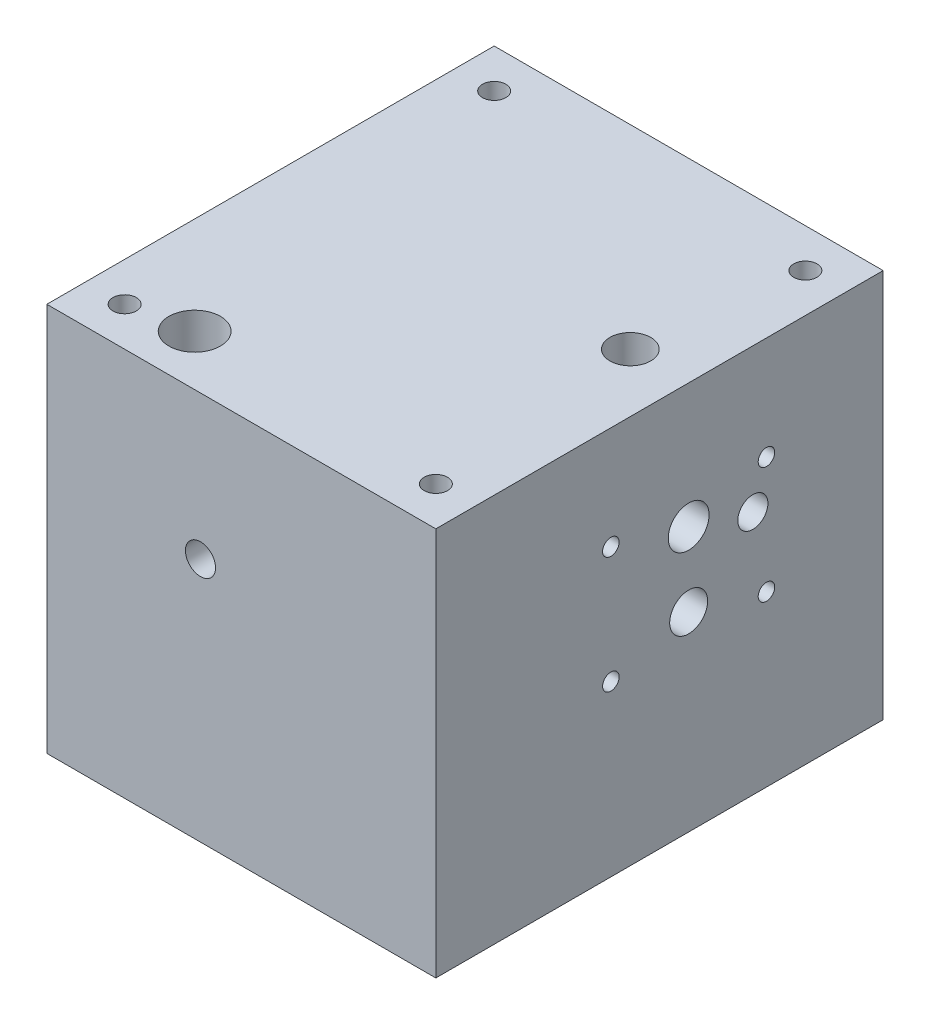
SolidWorks part; units mm, degrees
ref_plane "前视基准面" through (0, 0, 0) normal (0, 0, 1) x (1, 0, 0)
ref_plane "上视基准面" through (0, 0, 0) normal (0, 1, 0) x (1, 0, 0)
ref_plane "右视基准面" through (0, 0, 0) normal (1, 0, 0) x (0, 0, -1)
sketch "草图1" plane through (0, 0, 0) normal (0, 1, 0) x (1, 0, 0)
  line L1 (100, -100) -> (-100, -100)
  line L2 (100, -100) -> (100, 100)
  line L3 (100, 100) -> (-100, 100)
  line L4 (-100, -100) -> (-100, 100)
  line L5 (100, -100) -> (-100, 100) construction
  line L6 (100, 100) -> (-100, -100) construction
  point P0 (0, 0)
  dimension "D1" = 200
  dimension "D2" = 200
extrude "凸台-拉伸1" add sketch "草图1" along normal blind 200
sketch "草图9" plane through (100, 0, 0) normal (1, 0, 0) x (0, 0, -1)
  line L0 (0, 117) -> (0, 19.4773) construction
  line L1 (51, 74) -> (-51, 74)
  line L2 (51, 74) -> (51, 160)
  line L3 (51, 160) -> (-51, 160)
  line L4 (-51, 74) -> (-51, 160)
  line L5 (51, 74) -> (-51, 160) construction
  line L6 (51, 160) -> (-51, 74) construction
  line L7 (100, 200) -> (100, 0) construction
  line L8 (0, 117) -> (-57.0715, 117) construction
  line L9 (-100, 200) -> (100, 200) construction
  circle A0 centre (0, 136) radius 16.5
  circle A1 centre (0, 136) radius 16.5
  circle A2 centre (33, 126) radius 10
  circle A3 centre (0, 98) radius 16.5
  point P0 (-40, 147)
  point P1 (0, 117)
  point P2 (0, 117)
  point P7 (0, 136)
  point P8 (-40, 87)
  point P11 (0, 136)
  point P12 (40, 147)
  point P13 (40, 87)
  point P23 (33, 126)
  dimension "D14" = 33
  dimension "D15" = 33
  dimension "D19" = 20
  dimension "D21" = 33
  dimension "D1" = 86
  dimension "D2" = 102
  dimension "D3" = 100
  dimension "D4" = 40
  dimension "D5" = 40
  dimension "D6" = 30
  dimension "D7" = 30
  dimension "D8" = 30
  dimension "D9" = 30
  dimension "D10" = 11
  dimension "D11" = 40
  dimension "D12" = 19
  dimension "D13" = 19
  dimension "D16" = 40
  dimension "D17" = 9
  dimension "D18" = 33
  dimension "D20" = 38
hole_wizard "M10 螺纹孔1" positions "草图10" profile "草图11" tap size "M10" standard "GB"
sketch "草图10" plane through (100, 0, 0) normal (1, 0, 0) x (0, 0, -1)
  point P0 (-40, 87)
  point P3 (-40, 147)
  point P6 (40, 147)
  point P9 (40, 87)
sketch "草图11" plane through (100, 87, 40) normal (0, 1, 0) x (0, 0, -1)
  line L0 (0, 0) -> (0, 19.5537)
  line L1 (0, 19.5537) -> (4.25, 17)
  line L2 (4.25, 17) -> (4.25, 0)
  line L5 (4.25, 0) -> (0, 0)
  line L10 (0, 19.5537) -> (-4.25, 17) construction
  line L11 (0, -6.35) -> (0, 107.95) construction
  dimension "螺纹孔钻头直径" = 8.5
  dimension "螺纹孔钻头深度" = 17
  dimension "导头角度" = 118
cosmetic thread "孔螺蚊线5" parameters "D1"=17, "D2"=10
cosmetic thread "孔螺蚊线6" parameters "D1"=17, "D2"=10
cosmetic thread "孔螺蚊线7" parameters "D1"=17, "D2"=10
cosmetic thread "孔螺蚊线8" parameters "D1"=17, "D2"=10
sketch "草图12" plane through (0, 0, -100) normal (0, 0, -1) x (-1, 0, 0)
  line L0 (-100, 200) -> (-100, 0) construction
  line L1 (173, 43.5) -> (-173, 43.5)
  line L2 (173, 43.5) -> (173, 116.5)
  line L3 (173, 116.5) -> (-173, 116.5)
  line L4 (-173, 43.5) -> (-173, 116.5)
  line L5 (173, 43.5) -> (-173, 116.5) construction
  line L6 (173, 116.5) -> (-173, 43.5) construction
  line L7 (-68, 116.5) -> (-68, 43.5)
  line L8 (68, 116.5) -> (68, 43.5)
  line L9 (-100, 200) -> (100, 200) construction
  circle A0 centre (0, 62) radius 12.5
  circle A1 centre (0, 62) radius 9
  circle A2 centre (-21, 98) radius 9
  circle A3 centre (-21, 98) radius 12.5
  circle A4 centre (21, 98) radius 9
  circle A5 centre (21, 98) radius 12.5
  circle A6 centre (42, 62) radius 9
  circle A7 centre (42, 62) radius 12.5
  point P0 (0, 80)
  point P11 (44, 107)
  point P12 (21, 53)
  point P13 (-44, 107)
  point P14 (-21, 53)
  point P17 (0, 62)
  point P19 (-21, 98)
  point P22 (21, 98)
  point P31 (42, 62)
  dimension "D16" = 18
  dimension "D17" = 25
  dimension "D22" = 25
  dimension "D23" = 18
  dimension "D24" = 18
  dimension "D25" = 25
  dimension "D27" = 18
  dimension "D28" = 25
  dimension "D1" = 346
  dimension "D2" = 100
  dimension "D3" = 68
  dimension "D4" = 68
  dimension "D5" = 27
  dimension "D6" = 27
  dimension "D7" = 27
  dimension "D8" = 27
  dimension "D9" = 73
  dimension "D10" = 21
  dimension "D11" = 21
  dimension "D12" = 44
  dimension "D13" = 44
  dimension "D14" = 156.5
  dimension "D15" = 18
  dimension "D18" = 18
  dimension "D19" = 18
  dimension "D20" = 21
  dimension "D21" = 21
  dimension "D26" = 42
  dimension "D29" = 138
hole_wizard "M8 螺纹孔1" positions "草图13" profile "草图14" tap size "M8" standard "GB"
sketch "草图13" plane through (0, 0, -100) normal (0, 0, -1) x (-1, 0, 0)
  point P0 (-44, 107)
  point P3 (-21, 53)
  point P6 (21, 53)
  point P9 (44, 107)
sketch "草图14" plane through (44, 107, -100) normal (1, 0, 0) x (0, 1, 0)
  line L0 (0, 0) -> (0, 27.0429)
  line L1 (0, 27.0429) -> (3.4, 25)
  line L2 (3.4, 25) -> (3.4, 0)
  line L5 (3.4, 0) -> (0, 0)
  line L10 (0, 27.0429) -> (-3.4, 25) construction
  line L11 (0, -6.35) -> (0, 107.95) construction
  dimension "螺纹孔钻头直径" = 6.8
  dimension "螺纹孔钻头深度" = 25
  dimension "导头角度" = 118
cosmetic thread "孔螺蚊线9" parameters "D1"=16, "D2"=8
cosmetic thread "孔螺蚊线10" parameters "D1"=16, "D2"=8
cosmetic thread "孔螺蚊线11" parameters "D1"=16, "D2"=8
cosmetic thread "孔螺蚊线12" parameters "D1"=16, "D2"=8
sketch "草图16" plane through (-100, 0, 0) normal (-1, 0, 0) x (0, 0, 1)
  line L0 (-67.5744, 98.0404) -> (-50, 98.0404) construction
  line L5 (-50, 138) -> (56, 138)
  line L6 (-50, 138) -> (-50, 58)
  line L7 (-50, 58) -> (56, 58)
  line L8 (56, 138) -> (56, 58)
  line L9 (56, 98.0404) -> (97.1803, 98.0404) construction
  line L11 (-100, 200) -> (100, 200) construction
  circle A0 centre (0, 98.0404) radius 6
  circle A1 centre (0, 98.0404) radius 10
  circle A2 centre (-25, 98) radius 6
  circle A3 centre (-25, 98) radius 10
  point P4 (0, 98.0404)
  point P7 (23, 71.0404)
  point P8 (23, 125.0404)
  point P9 (-31, 125.0404)
  point P10 (-31, 71.0404)
  point P18 (-25, 98)
  dimension "D13" = 20
  dimension "D14" = 12
  dimension "D17" = 20
  dimension "D18" = 12
  dimension "D1" = 106
  dimension "D2" = 80
  dimension "D3" = 56
  dimension "D4" = 27
  dimension "D5" = 27
  dimension "D6" = 27
  dimension "D7" = 27
  dimension "D8" = 23
  dimension "D9" = 23
  dimension "D10" = 54
  dimension "D11" = 54
  dimension "D12" = 62
  dimension "D15" = 40
  dimension "D16" = 48
  dimension "D19" = 75
hole_wizard "M14 螺纹孔2" positions "草图19" profile "草图18" tap size "M14" standard "IS"
sketch "草图19" plane through (-100, 0, 0) normal (-1, 0, 0) x (0, 0, 1)
  point P0 (23, 125.0404)
  point P3 (-31, 125.0404)
  point P6 (-31, 71.0404)
  point P9 (23, 71.0404)
sketch "草图18" plane through (-100, 125.0404, 23) normal (0, 1, 0) x (0, 0, 1)
  line L0 (0, 0) -> (0, 20.6052)
  line L1 (0, 20.6052) -> (6, 17)
  line L2 (6, 17) -> (6, 0)
  line L5 (6, 0) -> (0, 0)
  line L10 (0, 20.6052) -> (-6, 17) construction
  line L11 (0, -6.35) -> (0, 107.95) construction
  dimension "螺纹孔钻头直径" = 12
  dimension "螺纹孔钻头深度" = 17
  dimension "导头角度" = 118
cosmetic thread "孔螺蚊线13" parameters "D1"=17, "D2"=14
cosmetic thread "孔螺蚊线14" parameters "D1"=17, "D2"=14
cosmetic thread "孔螺蚊线15" parameters "D1"=17, "D2"=14
cosmetic thread "孔螺蚊线16" parameters "D1"=17, "D2"=14
sketch "草图22" plane through (0, 200, 0) normal (0, 1, 0) x (1, 0, 0)
  line L0 (100, -100) -> (100, 100) construction
  line L1 (-173, 100) -> (173, 100) construction
  point P0 (70, 0)
  dimension "D1" = 30
  dimension "D2" = 100
hole_wizard "M24 螺纹孔的螺纹孔钻头1" positions "草图25" profile "草图26" hole size "M24" standard "IS"
sketch "草图25" plane through (0, 200, 0) normal (0, 1, 0) x (1, 0, 0)
  point P0 (70, 0)
sketch "草图26" plane through (70, 200, 0) normal (1, 0, 0) x (0, 0, 1)
  line L0 (0, 0) -> (0, 66.309)
  line L1 (0, 66.309) -> (10.5, 60)
  line L2 (10.5, 60) -> (10.5, 0)
  line L5 (10.5, 0) -> (0, 0)
  line L10 (0, 66.309) -> (-10.5, 60) construction
  line L11 (0, -6.35) -> (0, 107.95) construction
  dimension "孔直径" = 21
  dimension "孔深度" = 60
  dimension "导头角度" = 118
hole_wizard "M24 螺纹孔的螺纹孔钻头2" positions "草图29" profile "草图30" hole size "M24" standard "IS"
sketch "草图29" plane through (100, 0, 0) normal (1, 0, 0) x (0, 0, -1)
  point P0 (0, 136)
sketch "草图30" plane through (100, 136, 0) normal (0, 1, 0) x (0, 0, -1)
  line L0 (0, 0) -> (0, 48.309)
  line L1 (0, 48.309) -> (10.5, 42)
  line L2 (10.5, 42) -> (10.5, 0)
  line L5 (10.5, 0) -> (0, 0)
  line L10 (0, 48.309) -> (-10.5, 42) construction
  line L11 (0, -6.35) -> (0, 107.95) construction
  dimension "孔直径" = 21
  dimension "孔深度" = 42
  dimension "导头角度" = 118
hole_wizard "M22 螺纹孔的螺纹孔钻头1" positions "草图31" profile "草图32" hole size "M22" standard "IS"
sketch "草图31" plane through (0, 0, -100) normal (0, 0, -1) x (-1, 0, 0)
  point P0 (-21, 98)
sketch "草图32" plane through (21, 98, -100) normal (1, 0, 0) x (0, 1, 0)
  line L0 (0, 0) -> (0, 116.8584)
  line L1 (0, 116.8584) -> (9.75, 111)
  line L2 (9.75, 111) -> (9.75, 0)
  line L5 (9.75, 0) -> (0, 0)
  line L10 (0, 116.8584) -> (-9.75, 111) construction
  line L11 (0, -6.35) -> (0, 107.95) construction
  dimension "孔直径" = 19.5
  dimension "孔深度" = 111
  dimension "导头角度" = 118
hole_wizard "M22 螺纹孔的螺纹孔钻头3" positions "草图35" profile "草图36" hole size "M22" standard "IS"
sketch "草图35" plane through (-100, 0, 0) normal (-1, 0, 0) x (0, 0, 1)
  point P0 (-25, 98)
sketch "草图36" plane through (-100, 98, -25) normal (0, 1, 0) x (0, 0, 1)
  line L0 (0, 0) -> (0, 95.8584)
  line L1 (0, 95.8584) -> (9.75, 90)
  line L2 (9.75, 90) -> (9.75, 0)
  line L5 (9.75, 0) -> (0, 0)
  line L10 (0, 95.8584) -> (-9.75, 90) construction
  line L11 (0, -6.35) -> (0, 107.95) construction
  dimension "孔直径" = 19.5
  dimension "孔深度" = 90
  dimension "导头角度" = 118
hole_wizard "M22 螺纹孔的螺纹孔钻头4" positions "草图37" profile "草图38" hole size "M22" standard "IS"
sketch "草图37" plane through (0, 0, -100) normal (0, 0, -1) x (-1, 0, 0)
  point P0 (21, 98)
sketch "草图38" plane through (-21, 98, -100) normal (1, 0, 0) x (0, 1, 0)
  line L0 (0, 0) -> (0, 80.8584)
  line L1 (0, 80.8584) -> (9.75, 75)
  line L2 (9.75, 75) -> (9.75, 0)
  line L5 (9.75, 0) -> (0, 0)
  line L10 (0, 80.8584) -> (-9.75, 75) construction
  line L11 (0, -6.35) -> (0, 107.95) construction
  dimension "孔直径" = 19.5
  dimension "孔深度" = 75
  dimension "导头角度" = 118
hole_wizard "M18 螺纹孔的螺纹孔钻头1" positions "草图41" profile "草图42" hole size "M18" standard "GB"
sketch "草图41" plane through (-100, 0, 0) normal (-1, 0, 0) x (0, 0, 1)
  point P0 (0, 98.0404)
sketch "草图42" plane through (-100, 98.0404, 0) normal (0, 1, 0) x (0, 0, 1)
  line L0 (0, 0) -> (0, 92.6567)
  line L1 (0, 92.6567) -> (7.75, 88)
  line L2 (7.75, 88) -> (7.75, 0)
  line L5 (7.75, 0) -> (0, 0)
  line L10 (0, 92.6567) -> (-7.75, 88) construction
  line L11 (0, -6.35) -> (0, 107.95) construction
  dimension "孔直径" = 15.5
  dimension "孔深度" = 88
  dimension "导头角度" = 118
hole_wizard "M18 螺纹孔的螺纹孔钻头4" positions "草图48" profile "草图49" hole size "M18" standard "GB"
sketch "草图48" plane through (100, 0, 0) normal (1, 0, 0) x (0, 0, -1)
  point P0 (33, 126)
sketch "草图49" plane through (100, 126, -33) normal (0, 1, 0) x (0, 0, -1)
  line L0 (0, 0) -> (0, 134.6567)
  line L1 (0, 134.6567) -> (7.75, 130)
  line L2 (7.75, 130) -> (7.75, 0)
  line L5 (7.75, 0) -> (0, 0)
  line L10 (0, 134.6567) -> (-7.75, 130) construction
  line L11 (0, -6.35) -> (0, 107.95) construction
  dimension "孔直径" = 15.5
  dimension "孔深度" = 130
  dimension "导头角度" = 118
ref_plane "基准面2" through (0, 0, 0) normal (0, 0, 1) x (1, 0, 0)
sketch "草图50" plane through (0, 0, 0) normal (0, 0, 1) x (1, 0, 0)
  line L4 (-100, 0) -> (100, 0)
  line L5 (100, 0) -> (100, 200)
  line L6 (100, 200) -> (-100, 200)
  line L7 (-100, 200) -> (-100, 0)
  line L8 (-100, 0) -> (100, 0)
  line L9 (100, 0) -> (100, 200)
  line L10 (100, 200) -> (-100, 200)
  line L11 (-100, 200) -> (-100, 0)
  point P0 (-21, 126)
  dimension "D2" = 79
  dimension "D3" = 74
  dimension "D1" = 0
sketch "草图67" plane through (-100, 0, 0) normal (-1, 0, 0) x (0, 0, 1)
  line L0 (-100, 0) -> (100, 0) construction
  line L1 (19, 0) -> (-41, 0)
  line L2 (19, 0) -> (19, 53)
  line L3 (19, 53) -> (-41, 53)
  line L4 (-41, 0) -> (-41, 53)
  line L5 (-100, 200) -> (-100, 0) construction
  circle A0 centre (-25, 26.5) radius 5.5
  circle A1 centre (0, 26.5) radius 5.5
  point P6 (-9, 9)
  point P7 (-9, 44)
  point P8 (-29, 9)
  point P9 (-29, 44)
  point P10 (-25, 26.5)
  point P11 (0, 26.5)
  dimension "D14" = 11
  dimension "D15" = 11
  dimension "D1" = 60
  dimension "D2" = 53
  dimension "D3" = 12
  dimension "D4" = 32
  dimension "D5" = 12
  dimension "D6" = 32
  dimension "D7" = 9
  dimension "D8" = 9
  dimension "D9" = 9
  dimension "D10" = 9
  dimension "D11" = 26.5
  dimension "D12" = 16
  dimension "D13" = 100
  dimension "D16" = 75
hole_wizard "M22 螺纹孔的螺纹孔钻头5" positions "草图68" profile "草图69" hole size "M22" standard "GB"
sketch "草图68" plane through (100, 0, 0) normal (1, 0, 0) x (0, 0, -1)
  point P0 (0, 98)
sketch "草图69" plane through (100, 98, 0) normal (0, 1, 0) x (0, 0, -1)
  line L0 (0, 0) -> (0, 84.8584)
  line L1 (0, 84.8584) -> (9.75, 79)
  line L2 (9.75, 79) -> (9.75, 0)
  line L5 (9.75, 0) -> (0, 0)
  line L10 (0, 84.8584) -> (-9.75, 79) construction
  line L11 (0, -6.35) -> (0, 107.95) construction
  dimension "孔直径" = 19.5
  dimension "孔深度" = 79
  dimension "导头角度" = 118
hole_wizard "M10 螺纹孔2" positions "草图70" profile "草图71" tap size "M10" standard "GB"
sketch "草图70" plane through (-100, 0, 0) normal (-1, 0, 0) x (0, 0, 1)
  point P0 (-9, 44)
  point P3 (-29, 44)
  point P6 (-29, 9)
  point P9 (-9, 9)
sketch "草图71" plane through (-100, 44, -9) normal (0, 1, 0) x (0, 0, 1)
  line L0 (0, 0) -> (0, 12.5537)
  line L1 (0, 12.5537) -> (4.25, 10)
  line L2 (4.25, 10) -> (4.25, 0)
  line L5 (4.25, 0) -> (0, 0)
  line L10 (0, 12.5537) -> (-4.25, 10) construction
  line L11 (0, -6.35) -> (0, 107.95) construction
  dimension "螺纹孔钻头直径" = 8.5
  dimension "螺纹孔钻头深度" = 10
  dimension "导头角度" = 118
cosmetic thread "孔螺蚊线17" parameters "D1"=10, "D2"=10
cosmetic thread "孔螺蚊线18" parameters "D1"=10, "D2"=10
cosmetic thread "孔螺蚊线19" parameters "D1"=10, "D2"=10
cosmetic thread "孔螺蚊线20" parameters "D1"=10, "D2"=10
hole_wizard "M10 螺纹孔的螺纹孔钻头1" positions "草图72" profile "草图73" hole size "M10" standard "GB"
sketch "草图72" plane through (-100, 0, 0) normal (-1, 0, 0) x (0, 0, 1)
  point P0 (0, 26.5)
  point P3 (-25, 26.5)
sketch "草图73" plane through (-100, 26.5, 0) normal (0, 1, 0) x (0, 0, 1)
  line L0 (0, 0) -> (0, 42.5537)
  line L1 (0, 42.5537) -> (4.25, 40)
  line L2 (4.25, 40) -> (4.25, 0)
  line L5 (4.25, 0) -> (0, 0)
  line L10 (0, 42.5537) -> (-4.25, 40) construction
  line L11 (0, -6.35) -> (0, 107.95) construction
  dimension "孔直径" = 8.5
  dimension "孔深度" = 40
  dimension "导头角度" = 118
ref_plane "基准面3" through (0, 26.5, 0) normal (0, -1, 0) x (-1, 0, 0)
sketch "草图74" plane through (0, 26.5, 0) normal (0, -1, 0) x (-1, 0, 0)
  line L4 (100, -100) -> (100, 100)
  line L5 (100, 100) -> (-100, 100)
  line L6 (-100, 100) -> (-100, -100)
  line L7 (-100, -100) -> (100, -100)
  line L8 (100, -100) -> (100, 100)
  line L9 (100, 100) -> (-100, 100)
  line L10 (-100, 100) -> (-100, -100)
  line L11 (-100, -100) -> (100, -100)
  point P0 (64.25, 25)
  point P1 (64.25, 0)
  dimension "D2" = 35.75
  dimension "D3" = 35.75
  dimension "D4" = 100
  dimension "D5" = 75
  dimension "D1" = 0
hole_wizard "M10 螺纹孔的螺纹孔钻头2" positions "草图75" profile "草图76" hole size "M10" standard "GB"
sketch "草图75" plane through (0, 26.5, 0) normal (0, -1, 0) x (-1, 0, 0)
  point P0 (64.25, 0)
  point P3 (64.25, 25)
sketch "草图76" plane through (-64.25, 26.5, 0) normal (1, 0, 0) x (0, 0, -1)
  line L0 (0, 0) -> (0, 74.0537)
  line L1 (0, 74.0537) -> (4.25, 71.5)
  line L2 (4.25, 71.5) -> (4.25, 0)
  line L5 (4.25, 0) -> (0, 0)
  line L10 (0, 74.0537) -> (-4.25, 71.5) construction
  line L11 (0, -6.35) -> (0, 107.95) construction
  dimension "孔直径" = 8.5
  dimension "孔深度" = 71.5
  dimension "导头角度" = 118
hole_wizard "M24 螺纹孔的螺纹孔钻头3" positions "草图77" profile "草图78" hole size "M24" standard "GB"
sketch "草图77" plane through (0, 0, -100) normal (0, 0, -1) x (-1, 0, 0)
  point P0 (0, 62)
sketch "草图78" plane through (0, 62, -100) normal (1, 0, 0) x (0, 1, 0)
  line L0 (0, 0) -> (0, 46.809)
  line L1 (0, 46.809) -> (10.5, 40.5)
  line L2 (10.5, 40.5) -> (10.5, 0)
  line L5 (10.5, 0) -> (0, 0)
  line L10 (0, 46.809) -> (-10.5, 40.5) construction
  line L11 (0, -6.35) -> (0, 107.95) construction
  dimension "孔直径" = 21
  dimension "孔深度" = 40.5
  dimension "导头角度" = 118
sketch "草图79" plane through (0, 0, 0) normal (0, -1, 0) x (1, 0, 0)
  line L0 (100, 100) -> (100, -100) construction
  line L1 (100, -100) -> (-100, -100) construction
  point P0 (0, -70)
  dimension "D1" = 100
  dimension "D2" = 30
hole_wizard "M24 螺纹孔的螺纹孔钻头4" positions "草图80" profile "草图81" hole size "M24" standard "GB"
sketch "草图80" plane through (0, 0, 0) normal (0, -1, 0) x (-1, 0, 0)
  point P0 (0, 70)
sketch "草图81" plane through (0, 0, -70) normal (1, 0, 0) x (0, 0, -1)
  line L0 (0, 0) -> (0, 68.309)
  line L1 (0, 68.309) -> (10.5, 62)
  line L2 (10.5, 62) -> (10.5, 0)
  line L5 (10.5, 0) -> (0, 0)
  line L10 (0, 68.309) -> (-10.5, 62) construction
  line L11 (0, -6.35) -> (0, 107.95) construction
  dimension "孔直径" = 21
  dimension "孔深度" = 62
  dimension "导头角度" = 118
sketch "草图82" plane through (0, 0, 100) normal (0, 0, 1) x (1, 0, 0)
  line L0 (-100, 200) -> (100, 200) construction
  line L1 (-100, 200) -> (-100, 0) construction
  point P0 (-21, 126)
  dimension "D1" = 74
  dimension "D2" = 79
hole_wizard "M18 螺纹孔的螺纹孔钻头5" positions "草图83" profile "草图84" hole size "M18" standard "GB"
sketch "草图83" plane through (0, 0, 100) normal (0, 0, 1) x (1, 0, 0)
  point P0 (-21, 126)
sketch "草图84" plane through (-21, 126, 100) normal (1, 0, 0) x (0, -1, 0)
  line L0 (0, 0) -> (0, 137.6567)
  line L1 (0, 137.6567) -> (7.75, 133)
  line L2 (7.75, 133) -> (7.75, 0)
  line L5 (7.75, 0) -> (0, 0)
  line L10 (0, 137.6567) -> (-7.75, 133) construction
  line L11 (0, -6.35) -> (0, 107.95) construction
  dimension "孔直径" = 15.5
  dimension "孔深度" = 133
  dimension "导头角度" = 118
ref_plane "基准面4" through (0, 100, 0) normal (0, 1, 0) x (1, 0, 0)
sketch "草图85" plane through (0, 100, 0) normal (0, 1, 0) x (1, 0, 0)
  line L0 (-100, -19) -> (-100, 41) construction
  line L1 (-100, -100) -> (100, -100) construction
  point P0 (-21, 0)
  dimension "D1" = 79
  dimension "D2" = 100
hole_wizard "M18 螺纹孔的螺纹孔钻头6" positions "草图89" profile "草图90" hole size "M18" standard "GB"
sketch "草图89" plane through (0, 100, 0) normal (0, 1, 0) x (1, 0, 0)
  point P0 (-21, 0)
sketch "草图90" plane through (-21, 100, 0) normal (1, 0, 0) x (0, 0, -1)
  line L0 (0, 0) -> (0, 32.6567)
  line L1 (0, 32.6567) -> (7.75, 28)
  line L2 (7.75, 28) -> (7.75, 0)
  line L5 (7.75, 0) -> (0, 0)
  line L10 (0, 32.6567) -> (-7.75, 28) construction
  line L11 (0, -6.35) -> (0, 107.95) construction
  dimension "孔直径" = 15.5
  dimension "孔深度" = 28
  dimension "导头角度" = 118
hole_wizard "M18 螺纹孔的螺纹孔钻头7" positions "草图93" profile "草图94" hole size "M18" standard "GB"
sketch "草图93" plane through (0, 0, -100) normal (0, 0, -1) x (-1, 0, 0)
  point P0 (42, 62)
sketch "草图94" plane through (-42, 62, -100) normal (1, 0, 0) x (0, 1, 0)
  line L0 (0, 0) -> (0, 112.3567)
  line L1 (0, 112.3567) -> (7.75, 107.7)
  line L2 (7.75, 107.7) -> (7.75, 0)
  line L5 (7.75, 0) -> (0, 0)
  line L10 (0, 112.3567) -> (-7.75, 107.7) construction
  line L11 (0, -6.35) -> (0, 107.95) construction
  dimension "孔直径" = 15.5
  dimension "孔深度" = 107.7
  dimension "导头角度" = 118
ref_plane "基准面5" through (0, 62, 0) normal (0, -1, 0) x (-1, 0, 0)
sketch "草图96" plane through (0, 62, 0) normal (0, -1, 0) x (-1, 0, 0)
  line L0 (-100, 100) -> (100, 100) construction
  line L1 (100, 100) -> (100, -100) construction
  point P0 (42, 0)
  dimension "D1" = 100
  dimension "D2" = 58
hole_wizard "M18 螺纹孔的螺纹孔钻头8" positions "草图99" profile "草图100" hole size "M18" standard "GB"
sketch "草图99" plane through (0, 62, 0) normal (0, -1, 0) x (-1, 0, 0)
  point P0 (42, 0)
sketch "草图100" plane through (-42, 62, 0) normal (1, 0, 0) x (0, 0, -1)
  line L0 (0, 0) -> (0, 40.6567)
  line L1 (0, 40.6567) -> (7.75, 36)
  line L2 (7.75, 36) -> (7.75, 0)
  line L5 (7.75, 0) -> (0, 0)
  line L10 (0, 40.6567) -> (-7.75, 36) construction
  line L11 (0, -6.35) -> (0, 107.95) construction
  dimension "孔直径" = 15.5
  dimension "孔深度" = 36
  dimension "导头角度" = 118
sketch "草图101" plane through (0, 0, -100) normal (0, 0, -1) x (-1, 0, 0)
  point P0 (189.0213, 186.0801)
sketch "草图102" plane through (0, 0, -100) normal (0, 0, -1) x (-1, 0, 0)
  point P0 (-21, 160)
hole_wizard "M22 螺纹孔的螺纹孔钻头6" positions "草图105" profile "草图106" hole size "M22" standard "GB"
sketch "草图105" plane through (0, 0, -100) normal (0, 0, -1) x (-1, 0, 0)
  point P0 (-21, 160)
sketch "草图106" plane through (21, 160, -100) normal (1, 0, 0) x (0, 1, 0)
  line L0 (0, 0) -> (0, 45.6084)
  line L1 (0, 45.6084) -> (9.75, 39.75)
  line L2 (9.75, 39.75) -> (9.75, 0)
  line L5 (9.75, 0) -> (0, 0)
  line L10 (0, 45.6084) -> (-9.75, 39.75) construction
  line L11 (0, -6.35) -> (0, 107.95) construction
  dimension "孔直径" = 19.5
  dimension "孔深度" = 39.75
  dimension "导头角度" = 118
ref_plane "基准面6" through (0, 160, 0) normal (0, 1, 0) x (1, 0, 0)
sketch "草图107" plane through (0, 160, 0) normal (0, 1, 0) x (1, 0, 0)
  line L0 (-173, 100) -> (173, 100) construction
  point P0 (21, 70)
  dimension "D1" = 30
hole_wizard "M22 螺纹孔的螺纹孔钻头7" positions "草图108" profile "草图109" hole size "M22" standard "GB"
sketch "草图108" plane through (0, 160, 0) normal (0, 1, 0) x (1, 0, 0)
  point P0 (21, 70)
sketch "草图109" plane through (21, 160, -70) normal (1, 0, 0) x (0, 0, 1)
  line L0 (0, 0) -> (0, 67.8584)
  line L1 (0, 67.8584) -> (9.75, 62)
  line L2 (9.75, 62) -> (9.75, 0)
  line L5 (9.75, 0) -> (0, 0)
  line L10 (0, 67.8584) -> (-9.75, 62) construction
  line L11 (0, -6.35) -> (0, 107.95) construction
  dimension "孔直径" = 19.5
  dimension "孔深度" = 62
  dimension "导头角度" = 118
sketch "草图110" plane through (0, 0, 100) normal (0, 0, 1) x (1, 0, 0)
  line L4 (-100, 0) -> (100, 0)
  line L5 (100, 0) -> (100, 200)
  line L6 (100, 200) -> (-100, 200)
  line L7 (-100, 200) -> (-100, 0)
  line L8 (-100, 0) -> (100, 0)
  line L9 (100, 0) -> (100, 200)
  line L10 (100, 200) -> (-100, 200)
  line L11 (-100, 200) -> (-100, 0)
  dimension "D1" = 0
extrude "凸台-拉伸2" add sketch "草图110" along normal blind 30
sketch "草图111" plane through (0, 0, 0) normal (0, -1, 0) x (1, 0, 0)
  line L0 (100, 130) -> (100, -100) construction
  line L1 (-100, 130) -> (100, 130) construction
  line L2 (100, -100) -> (-100, -100) construction
  line L3 (-100, -100) -> (-100, 130) construction
  point P0 (80, 110)
  point P1 (-80, 110)
  point P2 (-80, -80)
  point P3 (80, -80)
  dimension "D1" = 20
  dimension "D2" = 20
  dimension "D3" = 20
  dimension "D4" = 20
  dimension "D5" = 20
  dimension "D6" = 20
  dimension "D7" = 20
  dimension "D8" = 20
hole_wizard "M14 螺纹孔的螺纹孔钻头2" positions "草图112" profile "草图113" hole size "M14" standard "GB" end condition through all
sketch "草图112" plane through (0, 0, 0) normal (0, -1, 0) x (-1, 0, 0)
  point P0 (-80, -110)
  point P3 (80, -110)
  point P6 (80, 80)
  point P9 (-80, 80)
sketch "草图113" plane through (80, 0, 110) normal (1, 0, 0) x (0, 0, -1)
  line L0 (0, 0) -> (0, 200)
  line L1 (0, 200) -> (6, 200)
  line L2 (6, 200) -> (6, 0)
  line L5 (6, 0) -> (0, 0)
  line L11 (0, -6.35) -> (0, 107.95) construction
  dimension "通孔孔直径" = 12
  dimension "通孔孔深度" = 200
sketch "草图114" plane through (0, 0, 130) normal (0, 0, 1) x (1, 0, 0)
  circle A0 centre (-21, 126) radius 7.75 construction
  circle A1 centre (-21, 126) radius 7.75
  point P1 (-173.9605, 299.4887)
  point P6 (-21, 126)
hole_wizard "M18 螺纹孔的螺纹孔钻头9" positions "草图115" profile "草图116" hole size "M18" standard "GB"
sketch "草图115" plane through (0, 0, 130) normal (0, 0, 1) x (1, 0, 0)
  point P0 (-21, 126)
sketch "草图116" plane through (-21, 126, 130) normal (1, 0, 0) x (0, -1, 0)
  line L0 (0, 0) -> (0, 66.6567)
  line L1 (0, 66.6567) -> (7.75, 62)
  line L2 (7.75, 62) -> (7.75, 0)
  line L5 (7.75, 0) -> (0, 0)
  line L10 (0, 66.6567) -> (-7.75, 62) construction
  line L11 (0, -6.35) -> (0, 107.95) construction
  dimension "孔直径" = 15.5
  dimension "孔深度" = 62
  dimension "导头角度" = 118
sketch "草图117" plane through (0, 0, 130) normal (0, 0, 1) x (1, 0, 0)
  line L1 (100, 200) -> (-100, 200) construction
  circle A0 centre (-21, 126) radius 7.75 construction
  circle A1 centre (-21, 126) radius 7.75
  point P3 (19, 126)
  point P4 (19, 126)
  dimension "D1" = 40
  dimension "D2" = 74
  dimension "D3" = 74
sketch "草图120" plane through (0, 0, 0) normal (0, -1, 0) x (1, 0, 0)
  line L0 (-100, -100) -> (-100, 130) construction
  line L1 (-100, 130) -> (100, 130) construction
  point P0 (-50, 104)
  dimension "D1" = 50
  dimension "D2" = 26
hole_wizard "M30 螺纹孔的螺纹孔钻头1" positions "草图121" profile "草图122" hole size "M30" standard "GB" end condition through all
sketch "草图121" plane through (0, 0, 0) normal (0, -1, 0) x (-1, 0, 0)
  point P0 (50, -104)
sketch "草图122" plane through (-50, 0, 104) normal (1, 0, 0) x (0, 0, -1)
  line L0 (0, 0) -> (0, 200)
  line L1 (0, 200) -> (13.25, 200)
  line L2 (13.25, 200) -> (13.25, 0)
  line L5 (13.25, 0) -> (0, 0)
  line L11 (0, -6.35) -> (0, 107.95) construction
  dimension "通孔孔直径" = 26.5
  dimension "通孔孔深度" = 200
